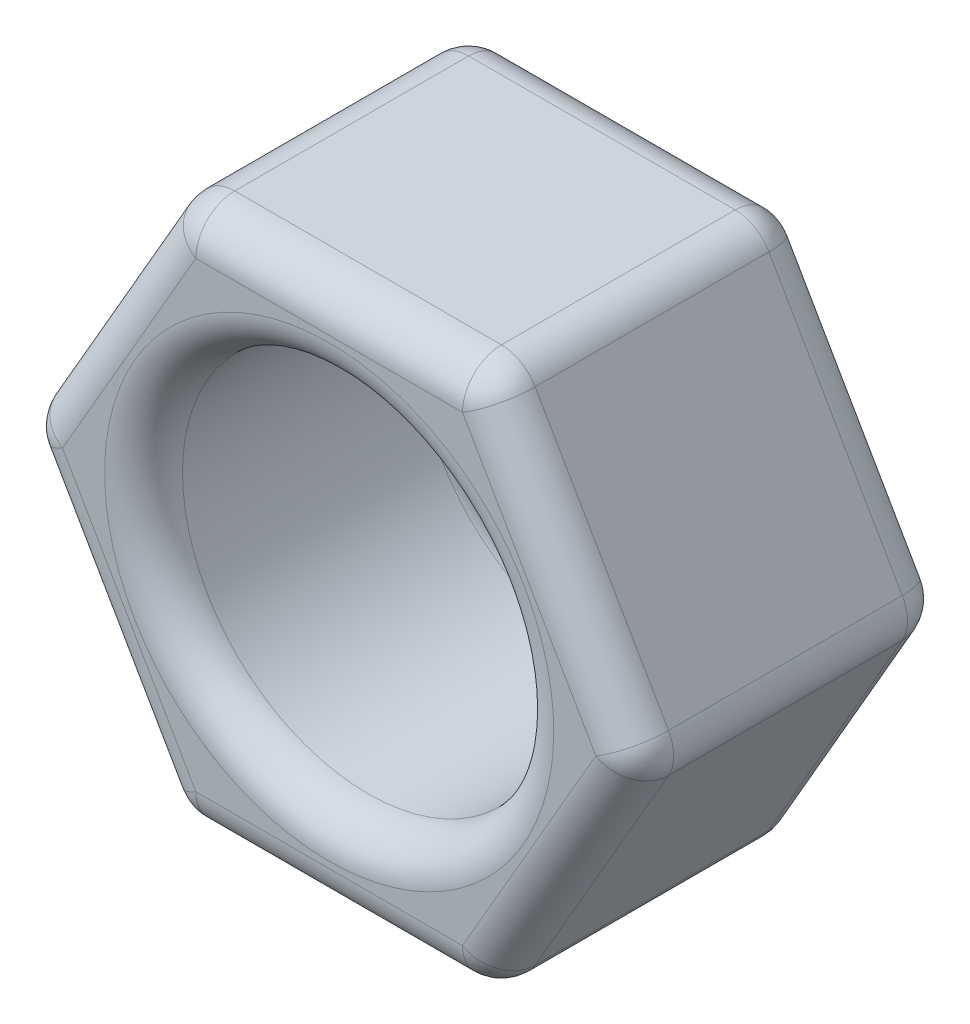
SolidWorks part; units mm, degrees
ref_plane "Plano frontal" through (0, 0, 0) normal (0, 0, 1) x (1, 0, 0)
ref_plane "Plano superior" through (0, 0, 0) normal (0, 1, 0) x (1, 0, 0)
ref_plane "Plano direito" through (0, 0, 0) normal (1, 0, 0) x (0, 0, -1)
sketch "Esboço1" plane through (0, 0, 0) normal (0, 0, 1) x (1, 0, 0)
  line L1 (8, 0) -> (4, 6.9282)
  line L2 (4, 6.9282) -> (-4, 6.9282)
  line L3 (-4, 6.9282) -> (-8, 0)
  line L4 (-8, 0) -> (-4, -6.9282)
  line L5 (-4, -6.9282) -> (4, -6.9282)
  line L6 (4, -6.9282) -> (8, 0)
  circle A0 centre (0, 0) radius 6.9282 construction
  circle A1 centre (0, 0) radius 4.765
  dimension "D2" = 9.53
  dimension "D1" = 16
extrude "Ressalto-extrusão1" add sketch "Esboço1" along normal blind 8
fillet "Filete1" radius 1 20 edges at (8, 0, 4) (4, 6.9282, 4) (-4, 6.9282, 4) (-8, 0, 4) (-4, -6.9282, 4) (4, -6.9282, 4) (0, -6.9282, 8) (-6, -3.4641, 8) (-6, 3.4641, 8) (0, 6.9282, 8) (6, 3.4641, 8) (6, -3.4641, 8) (0, -6.9282, 0) (-6, -3.4641, 0) (-6, 3.4641, 0) (0, 6.9282, 0) (6, 3.4641, 0) (6, -3.4641, 0) (4.765, 0, 8) (4.765, 0, 0)
